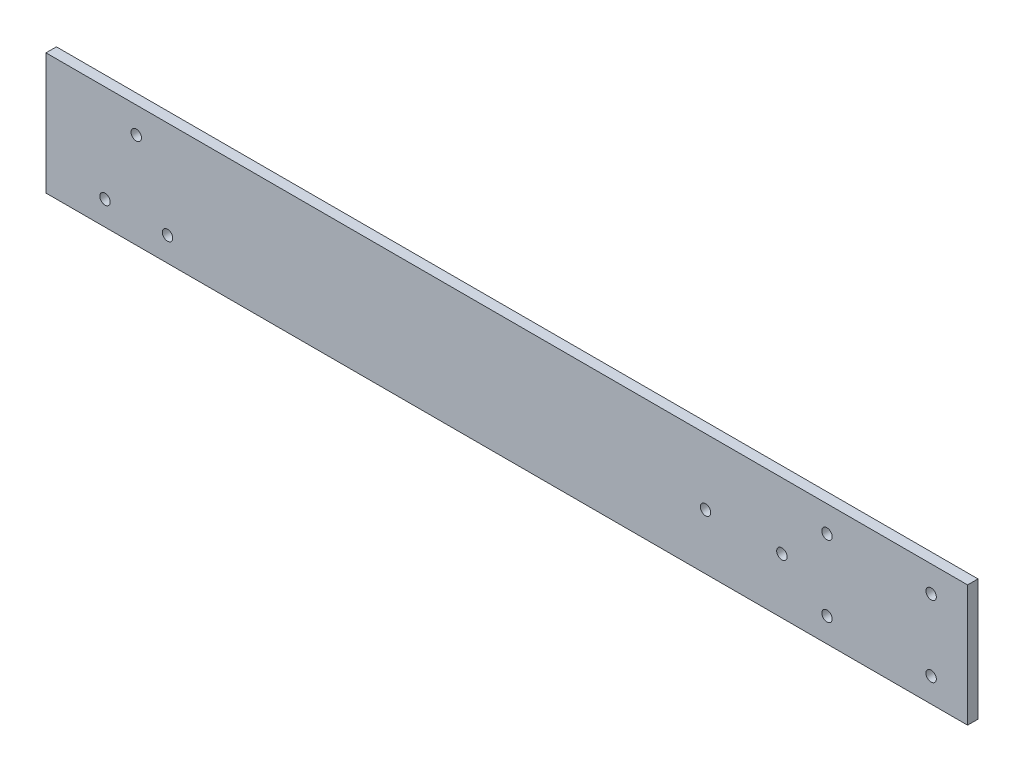
SolidWorks part; units mm, degrees
material "MDF"
ref_plane "Alzado" through (0, 0, 0) normal (0, 0, 1) x (1, 0, 0)
ref_plane "Planta" through (0, 0, 0) normal (0, 1, 0) x (1, 0, 0)
ref_plane "Vista lateral" through (0, 0, 0) normal (1, 0, 0) x (0, 0, -1)
sketch "Croquis1" plane through (0, 0, 0) normal (0, 0, 1) x (1, 0, 0)
  line L1 (-132.75, 17.5) -> (132.75, 17.5)
  line L2 (-132.75, 17.5) -> (-132.75, -17.5)
  line L3 (-132.75, -17.5) -> (132.75, -17.5)
  line L4 (132.75, 17.5) -> (132.75, -17.5)
  line L5 (-132.75, 17.5) -> (132.75, -17.5) construction
  line L6 (-132.75, -17.5) -> (132.75, 17.5) construction
  circle A0 centre (79.25, -1.5) radius 1.5
  circle A1 centre (-115.75, -10.5) radius 1.5
  circle A2 centre (-97.75, -10.5) radius 1.5
  circle A3 centre (-106.75, 10) radius 1.5
  circle A4 centre (122.25, 10) radius 1.5
  circle A5 centre (92.25, 10) radius 1.5
  circle A6 centre (92.25, -10.5) radius 1.5
  circle A7 centre (122.25, -10.5) radius 1.5
  circle A8 centre (57.25, -1.5) radius 1.5
  point P0 (0, 0)
  dimension "D3" = 3
  dimension "D1" = 35
  dimension "D2" = 265.5
  dimension "D4" = 27.5
  dimension "D5" = 26
  dimension "D6" = 7
  dimension "D7" = 17
  dimension "D8" = 18
  dimension "D9" = 10.5
  dimension "D10" = 27.5
  dimension "D13" = 30
  dimension "D14" = 7
  dimension "D15" = 16
  dimension "D16" = 53.5
  dimension "D17" = 22
  dimension "D11" = 2
  dimension "D12" = 2
extrude "Saliente-Extruir1" add sketch "Croquis1" along normal blind 3
